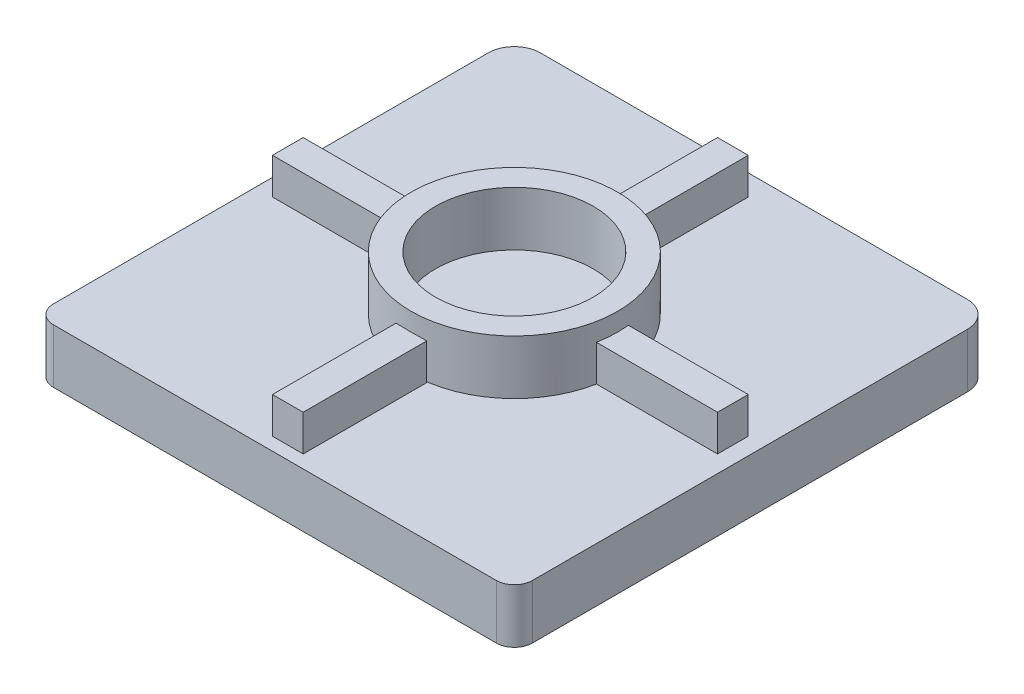
SolidWorks part; units mm, degrees
ref_plane "Front Plane" through (0, 0, 0) normal (0, 0, 1) x (1, 0, 0)
ref_plane "Top Plane" through (0, 0, 0) normal (0, 1, 0) x (1, 0, 0)
ref_plane "Right Plane" through (0, 0, 0) normal (1, 0, 0) x (0, 0, -1)
sketch "Sketch1" plane through (0, 0, 0) normal (0, 1, 0) x (1, 0, 0)
  line L0 (80.9528, -6.9331) -> (3.175, -6.9331)
  line L2 (0, -3.7581) -> (0, 72.6121)
  line L3 (4.572, 77.1841) -> (79.5558, 77.1841)
  line L4 (84.1278, -3.7581) -> (84.1278, 72.6121)
  arc A0 (4.572, 77.1841) -> (0, 72.6121) centre (4.572, 72.6121) ccw
  arc A1 (84.1278, 72.6121) -> (79.5558, 77.1841) centre (79.5558, 72.6121) ccw
  arc A2 (3.175, -6.9331) -> (0, -3.7581) centre (3.175, -3.7581) cw
  arc A3 (84.1278, -3.7581) -> (80.9528, -6.9331) centre (80.9528, -3.7581) cw
  point P13 (0, 0)
  dimension "D1" = 4.572
  dimension "D2" = 3.175
extrude "Extrude1" add sketch "Sketch1" against normal blind 9.525
sketch "Sketch2" plane through (0, 0, 0) normal (0, 1, 0) x (1, 0, 0)
  circle A0 centre (42.0639, 35.1308) radius 18.1352
  circle A1 centre (42.0639, 35.1308) radius 13.8499
extrude "Extrude2" add sketch "Sketch2" along normal blind 9.525
sketch "Sketch4" plane through (0, 0, 0) normal (0, 1, 0) x (1, 0, 0)
  line L0 (42.0639, 77.1947) -> (42.0639, -6.9331) construction
  line L3 (0, 34.427) -> (84.1278, 34.427) construction
  line L4 (0, 72.6121) -> (0, -3.7581) construction
  line L5 (84.1278, -3.7581) -> (84.1278, 72.6121) construction
sketch "Sketch5" plane through (0, 0, 0) normal (0, 1, 0) x (1, 0, 0)
  line L0 (0, 34.427) -> (84.1278, 34.427) construction
  line L1 (59.4541, 37.1238) -> (81.1462, 37.1238)
  line L2 (59.4541, 37.1238) -> (59.4541, 31.7302)
  line L3 (59.4541, 31.7302) -> (81.1462, 31.7302)
  line L4 (81.1462, 37.1238) -> (81.1462, 31.7302)
  line L5 (44.7607, -4.6553) -> (39.3671, -4.6553)
  line L6 (39.3671, 17.0368) -> (39.3671, -4.6553)
  line L7 (44.7607, 17.0368) -> (39.3671, 17.0368)
  line L8 (44.7607, 17.0368) -> (44.7607, -4.6553)
  line L9 (2.9816, 31.7302) -> (2.9816, 37.1238)
  line L10 (24.6737, 37.1238) -> (2.9816, 37.1238)
  line L11 (24.6737, 31.7302) -> (24.6737, 37.1238)
  line L12 (24.6737, 31.7302) -> (2.9816, 31.7302)
  line L13 (39.3671, 73.5094) -> (44.7607, 73.5094)
  line L14 (44.7607, 51.8172) -> (44.7607, 73.5094)
  line L15 (39.3671, 51.8172) -> (44.7607, 51.8172)
  line L16 (39.3671, 51.8172) -> (39.3671, 73.5094)
  point P0 (70.3002, 34.427)
extrude "Extrude4" add sketch "Sketch5" along normal blind 6.35
